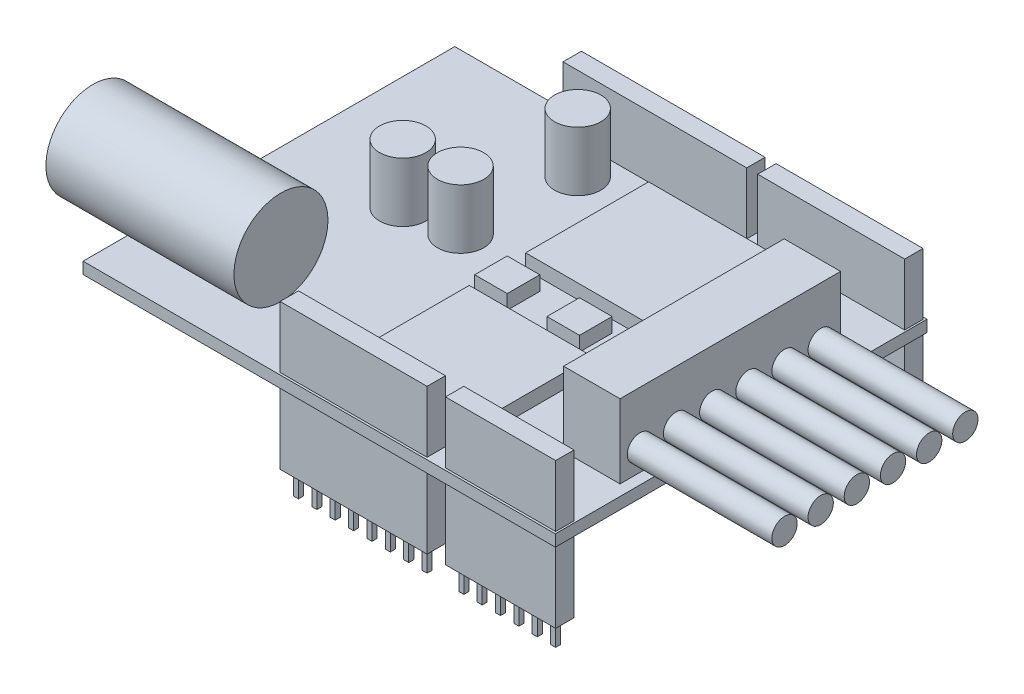
SolidWorks part; units mm, degrees
ref_plane "Plan de face" through (0, 0, 0) normal (0, 0, 1) x (1, 0, 0)
ref_plane "Plan de dessus" through (0, 0, 0) normal (0, 1, 0) x (1, 0, 0)
ref_plane "Plan de droite" through (0, 0, 0) normal (1, 0, 0) x (0, 0, -1)
sketch "Esquisse1" plane through (0, 0, 0) normal (0, 1, 0) x (1, 0, 0)
  line L1 (-32.65, 25.7) -> (32.65, 25.7)
  line L2 (-32.65, 25.7) -> (-32.65, -25.7)
  line L3 (-32.65, -25.7) -> (32.65, -25.7)
  line L4 (32.65, 25.7) -> (32.65, -25.7)
  point P4 (0, 25.7)
  point P6 (-32.65, 0)
  dimension "D1" = 65.3
  dimension "D2" = 51.4
extrude "Boss.-Extru.1" add sketch "Esquisse1" along normal blind 1.6
sketch "Esquisse2" plane through (0, 1.6, 0) normal (0, 1, 0) x (1, 0, 0)
  line L0 (0, 0) -> (8.1488, 0) construction
  line L1 (-1.05, 20.9) -> (15.95, 20.9)
  line L2 (-1.05, 20.9) -> (-1.05, 3.9)
  line L3 (-1.05, 3.9) -> (15.95, 3.9)
  line L4 (15.95, 20.9) -> (15.95, 3.9)
  line L5 (-1.05, -3.9) -> (15.95, -3.9)
  line L6 (15.95, -20.9) -> (15.95, -3.9)
  line L7 (-1.05, -20.9) -> (15.95, -20.9)
  line L8 (-1.05, -20.9) -> (-1.05, -3.9)
  line L9 (-32.65, 25.7) -> (-32.65, -25.7) construction
  line L10 (-1.95, 2.25) -> (2.55, 2.25)
  line L11 (-1.95, 2.25) -> (-1.95, -2.25)
  line L12 (-1.95, -2.25) -> (2.55, -2.25)
  line L13 (2.55, 2.25) -> (2.55, -2.25)
  line L14 (8.05, 2.25) -> (12.55, 2.25)
  line L15 (8.05, 2.25) -> (8.05, -2.25)
  line L16 (8.05, -2.25) -> (12.55, -2.25)
  line L17 (12.55, 2.25) -> (12.55, -2.25)
  point P15 (2.55, 0)
  dimension "D1" = 17
  dimension "D2" = 4.5
  dimension "D3" = 7.8
  dimension "D4" = 31.6
  dimension "D5" = 5.5
  dimension "D6" = 30.7
extrude "Boss.-Extru.2" add sketch "Esquisse2" along normal blind 2 separate body
sketch "Esquisse3" plane through (0, 1.6, 0) normal (0, 1, 0) x (1, 0, 0)
  line L0 (-32.65, 25.7) -> (-32.65, -25.7) construction
  line L1 (32.65, 25.7) -> (-32.65, 25.7) construction
  circle A0 centre (-8.55, 18.6) radius 3.2
  circle A1 centre (-9.75, 3.6) radius 3.2
  circle A2 centre (-16.95, 2.8) radius 3.2
  dimension "D1" = 6.4
  dimension "D2" = 15.7
  dimension "D3" = 22.9
  dimension "D4" = 24.1
  dimension "D5" = 7.1
  dimension "D6" = 22.1
  dimension "D7" = 22.9
extrude "Boss.-Extru.3" add sketch "Esquisse3" along normal blind 8.2 separate body
sketch "Esquisse4" plane through (0, 1.6, 0) normal (0, 1, 0) x (1, 0, 0)
  line L0 (32.65, -25.7) -> (32.65, 25.7) construction
  line L1 (23.35, 15.25) -> (31.15, 15.25)
  line L2 (23.35, 15.25) -> (23.35, -15.25)
  line L3 (23.35, -15.25) -> (31.15, -15.25)
  line L4 (31.15, 15.25) -> (31.15, -15.25)
  point P4 (23.35, 0)
  dimension "D1" = 7.8
  dimension "D2" = 30.5
  dimension "D3" = 1.5
extrude "Boss.-Extru.4" add sketch "Esquisse4" along normal blind 10.2 separate body
sketch "Esquisse5" plane through (31.15, 0, 0) normal (1, 0, 0) x (0, 0, -1)
  line L0 (0, 0) -> (0, 9.7249) construction
  line L1 (-15.25, 1.6) -> (15.25, 1.6) construction
  circle A0 centre (2.5, 4.6) radius 1.75
  circle A1 centre (-2.5, 4.6) radius 1.75
  circle A2 centre (7.5, 4.6) radius 1.75
  circle A3 centre (12.5, 4.6) radius 1.75
  circle A4 centre (-2.5, 4.6) radius 1.75
  circle A5 centre (2.5, 4.6) radius 1.75
  circle A6 centre (-12.5, 4.6) radius 1.75
  circle A7 centre (-7.5, 4.6) radius 1.75
  dimension "D2" = 3.5
  dimension "D1" = 3
  dimension "D3" = 5
  dimension "D4" = 2
  dimension "D5" = 2
extrude "Boss.-Extru.5" add sketch "Esquisse5" along normal blind 20 separate body contours A3 | A2 | A0 | A1 | A7 | A6
sketch "Esquisse6" plane through (-32.65, 0, 0) normal (-1, 0, 0) x (0, 0, 1)
  circle A0 centre (17.8373, 9.0901) radius 6.5
  dimension "D1" = 13
extrude "Boss.-Extru.6" add sketch "Esquisse6" against normal blind 19.5 and the other way blind 6.5 separate body
sketch "Esquisse7" plane through (0, 1.6, 0) normal (0, 1, 0) x (1, 0, 0)
  line L0 (0, 0) -> (32.4, 0) construction
  line L1 (12.08, 25.4) -> (32.4, 25.4)
  line L2 (12.08, 25.4) -> (12.08, 22.86)
  line L3 (12.08, 22.86) -> (32.4, 22.86)
  line L4 (32.4, 25.4) -> (32.4, 22.86)
  line L5 (32.4, -22.86) -> (32.4, 22.86) construction
  line L6 (10.56, 25.4) -> (-14.84, 25.4)
  line L7 (10.56, 25.4) -> (10.56, 22.86)
  line L8 (10.56, 22.86) -> (-14.84, 22.86)
  line L9 (-14.84, 25.4) -> (-14.84, 22.86)
  line L10 (17.16, -22.86) -> (32.4, -22.86)
  line L11 (17.16, -22.86) -> (17.16, -25.4)
  line L12 (17.16, -25.4) -> (32.4, -25.4)
  line L13 (32.4, -22.86) -> (32.4, -25.4)
  line L14 (-5.7, -22.86) -> (14.62, -22.86)
  line L15 (-5.7, -22.86) -> (-5.7, -25.4)
  line L16 (-5.7, -25.4) -> (14.62, -25.4)
  line L17 (14.62, -22.86) -> (14.62, -25.4)
  line L18 (32.65, -25.7) -> (32.65, 25.7) construction
  point P19 (32.4, -24.13)
  point P20 (32.4, 24.13)
  dimension "D1" = 2.54
  dimension "D2" = 20.32
  dimension "D3" = 25.4
  dimension "D4" = 1.52
  dimension "D5" = 15.24
  dimension "D6" = 20.32
  dimension "D7" = 2.54
  dimension "D8" = 48.26
  dimension "D9" = 0.25
extrude "Boss.-Extru.7" add sketch "Esquisse7" along normal blind 8.5 and the other way blind 11.6 separate body
sketch "Esquisse8" plane through (0, 0, 0) normal (0, -1, 0) x (1, 0, 0)
  line L0 (12.08, -25.4) -> (12.08, -22.86) construction
  line L1 (13, -24.48) -> (13.7, -24.48)
  line L2 (13, -24.48) -> (13, -23.78)
  line L3 (13, -23.78) -> (13.7, -23.78)
  line L4 (13.7, -24.48) -> (13.7, -23.78)
  line L5 (16.24, -24.48) -> (16.24, -23.78)
  line L6 (15.54, -23.78) -> (16.24, -23.78)
  line L7 (15.54, -24.48) -> (15.54, -23.78)
  line L8 (15.54, -24.48) -> (16.24, -24.48)
  line L9 (18.78, -24.48) -> (18.78, -23.78)
  line L10 (18.08, -23.78) -> (18.78, -23.78)
  line L11 (18.08, -24.48) -> (18.08, -23.78)
  line L12 (18.08, -24.48) -> (18.78, -24.48)
  line L13 (21.32, -24.48) -> (21.32, -23.78)
  line L14 (20.62, -23.78) -> (21.32, -23.78)
  line L15 (20.62, -24.48) -> (20.62, -23.78)
  line L16 (20.62, -24.48) -> (21.32, -24.48)
  line L17 (23.86, -24.48) -> (23.86, -23.78)
  line L18 (23.16, -23.78) -> (23.86, -23.78)
  line L19 (23.16, -24.48) -> (23.16, -23.78)
  line L20 (23.16, -24.48) -> (23.86, -24.48)
  line L21 (26.4, -24.48) -> (26.4, -23.78)
  line L22 (25.7, -23.78) -> (26.4, -23.78)
  line L23 (25.7, -24.48) -> (25.7, -23.78)
  line L24 (25.7, -24.48) -> (26.4, -24.48)
  line L25 (28.94, -24.48) -> (28.94, -23.78)
  line L26 (28.24, -23.78) -> (28.94, -23.78)
  line L27 (28.24, -24.48) -> (28.24, -23.78)
  line L28 (28.24, -24.48) -> (28.94, -24.48)
  line L29 (31.48, -24.48) -> (31.48, -23.78)
  line L30 (30.78, -23.78) -> (31.48, -23.78)
  line L31 (30.78, -24.48) -> (30.78, -23.78)
  line L32 (30.78, -24.48) -> (31.48, -24.48)
  line L33 (10.56, -22.86) -> (10.56, -25.4) construction
  line L34 (9.64, -24.48) -> (8.94, -24.48)
  line L35 (9.64, -24.48) -> (9.64, -23.78)
  line L36 (9.64, -23.78) -> (8.94, -23.78)
  line L37 (8.94, -24.48) -> (8.94, -23.78)
  line L38 (7.1, -23.78) -> (6.4, -23.78)
  line L39 (6.4, -24.48) -> (6.4, -23.78)
  line L40 (7.1, -24.48) -> (6.4, -24.48)
  line L41 (7.1, -24.48) -> (7.1, -23.78)
  line L42 (4.56, -23.78) -> (3.86, -23.78)
  line L43 (3.86, -24.48) -> (3.86, -23.78)
  line L44 (4.56, -24.48) -> (3.86, -24.48)
  line L45 (4.56, -24.48) -> (4.56, -23.78)
  line L46 (2.02, -23.78) -> (1.32, -23.78)
  line L47 (1.32, -24.48) -> (1.32, -23.78)
  line L48 (2.02, -24.48) -> (1.32, -24.48)
  line L49 (2.02, -24.48) -> (2.02, -23.78)
  line L50 (-0.52, -23.78) -> (-1.22, -23.78)
  line L51 (-1.22, -24.48) -> (-1.22, -23.78)
  line L52 (-0.52, -24.48) -> (-1.22, -24.48)
  line L53 (-0.52, -24.48) -> (-0.52, -23.78)
  line L54 (-3.06, -23.78) -> (-3.76, -23.78)
  line L55 (-3.76, -24.48) -> (-3.76, -23.78)
  line L56 (-3.06, -24.48) -> (-3.76, -24.48)
  line L57 (-3.06, -24.48) -> (-3.06, -23.78)
  line L58 (-5.6, -23.78) -> (-6.3, -23.78)
  line L59 (-6.3, -24.48) -> (-6.3, -23.78)
  line L60 (-5.6, -24.48) -> (-6.3, -24.48)
  line L61 (-5.6, -24.48) -> (-5.6, -23.78)
  line L62 (-8.14, -23.78) -> (-8.84, -23.78)
  line L63 (-8.84, -24.48) -> (-8.84, -23.78)
  line L64 (-8.14, -24.48) -> (-8.84, -24.48)
  line L65 (-8.14, -24.48) -> (-8.14, -23.78)
  line L66 (-10.68, -23.78) -> (-11.38, -23.78)
  line L67 (-11.38, -24.48) -> (-11.38, -23.78)
  line L68 (-10.68, -24.48) -> (-11.38, -24.48)
  line L69 (-10.68, -24.48) -> (-10.68, -23.78)
  line L70 (-13.22, -23.78) -> (-13.92, -23.78)
  line L71 (-13.92, -24.48) -> (-13.92, -23.78)
  line L72 (-13.22, -24.48) -> (-13.92, -24.48)
  line L73 (-13.22, -24.48) -> (-13.22, -23.78)
  line L74 (14.62, 25.4) -> (14.62, 22.86) construction
  line L75 (18.08, 23.78) -> (18.78, 23.78)
  line L76 (18.08, 23.78) -> (18.08, 24.48)
  line L77 (18.08, 24.48) -> (18.78, 24.48)
  line L78 (18.78, 23.78) -> (18.78, 24.48)
  line L79 (13.7, 23.78) -> (13, 23.78)
  line L80 (13.7, 23.78) -> (13.7, 24.48)
  line L81 (13.7, 24.48) -> (13, 24.48)
  line L82 (13, 23.78) -> (13, 24.48)
  line L83 (17.16, 22.86) -> (17.16, 25.4) construction
  line L84 (21.32, 23.78) -> (21.32, 24.48)
  line L85 (20.62, 23.78) -> (21.32, 23.78)
  line L86 (20.62, 23.78) -> (20.62, 24.48)
  line L87 (20.62, 24.48) -> (21.32, 24.48)
  line L88 (23.86, 23.78) -> (23.86, 24.48)
  line L89 (23.16, 23.78) -> (23.86, 23.78)
  line L90 (23.16, 23.78) -> (23.16, 24.48)
  line L91 (23.16, 24.48) -> (23.86, 24.48)
  line L92 (26.4, 23.78) -> (26.4, 24.48)
  line L93 (25.7, 23.78) -> (26.4, 23.78)
  line L94 (25.7, 23.78) -> (25.7, 24.48)
  line L95 (25.7, 24.48) -> (26.4, 24.48)
  line L96 (28.94, 23.78) -> (28.94, 24.48)
  line L97 (28.24, 23.78) -> (28.94, 23.78)
  line L98 (28.24, 23.78) -> (28.24, 24.48)
  line L99 (28.24, 24.48) -> (28.94, 24.48)
  line L100 (31.48, 23.78) -> (31.48, 24.48)
  line L101 (30.78, 23.78) -> (31.48, 23.78)
  line L102 (30.78, 23.78) -> (30.78, 24.48)
  line L103 (30.78, 24.48) -> (31.48, 24.48)
  line L104 (11.16, 23.78) -> (10.46, 23.78)
  line L105 (11.16, 23.78) -> (11.16, 24.48)
  line L106 (11.16, 24.48) -> (10.46, 24.48)
  line L107 (10.46, 23.78) -> (10.46, 24.48)
  line L108 (8.62, 23.78) -> (7.92, 23.78)
  line L109 (8.62, 23.78) -> (8.62, 24.48)
  line L110 (8.62, 24.48) -> (7.92, 24.48)
  line L111 (7.92, 23.78) -> (7.92, 24.48)
  line L112 (6.08, 23.78) -> (5.38, 23.78)
  line L113 (6.08, 23.78) -> (6.08, 24.48)
  line L114 (6.08, 24.48) -> (5.38, 24.48)
  line L115 (5.38, 23.78) -> (5.38, 24.48)
  line L116 (3.54, 23.78) -> (2.84, 23.78)
  line L117 (3.54, 23.78) -> (3.54, 24.48)
  line L118 (3.54, 24.48) -> (2.84, 24.48)
  line L119 (2.84, 23.78) -> (2.84, 24.48)
  line L120 (1, 23.78) -> (0.3, 23.78)
  line L121 (1, 23.78) -> (1, 24.48)
  line L122 (1, 24.48) -> (0.3, 24.48)
  line L123 (0.3, 23.78) -> (0.3, 24.48)
  line L124 (-1.54, 23.78) -> (-2.24, 23.78)
  line L125 (-1.54, 23.78) -> (-1.54, 24.48)
  line L126 (-1.54, 24.48) -> (-2.24, 24.48)
  line L127 (-2.24, 23.78) -> (-2.24, 24.48)
  line L128 (-4.08, 23.78) -> (-4.78, 23.78)
  line L129 (-4.08, 23.78) -> (-4.08, 24.48)
  line L130 (-4.08, 24.48) -> (-4.78, 24.48)
  line L131 (-4.78, 23.78) -> (-4.78, 24.48)
  point P6 (12.08, -24.13)
  point P7 (13, -24.13)
  point P8 (13.35, -23.78)
  point P43 (10.56, -24.13)
  point P44 (9.64, -24.13)
  point P45 (9.29, -24.48)
  point P93 (14.62, 24.13)
  point P94 (13.7, 24.13)
  point P97 (17.16, 24.13)
  point P98 (18.08, 24.13)
  point P99 (13.35, 23.78)
  point P100 (18.43, 23.78)
  dimension "D1" = 0.7
  dimension "D2" = 1.27
  dimension "D4" = 1.27
  dimension "D6" = 1.27
  dimension "D7" = 1.27
  dimension "D3" = 8
  dimension "D5" = 10
  dimension "D8" = 6
  dimension "D9" = 8
extrude "Boss.-Extru.8" add sketch "Esquisse8" along normal blind 13.2
equation "\"D4@Esquisse8\"=\"D2@Esquisse8\""
equation "\"D6@Esquisse8\"=\"D2@Esquisse8\""
equation "\"D7@Esquisse8\"=\"D2@Esquisse8\""
